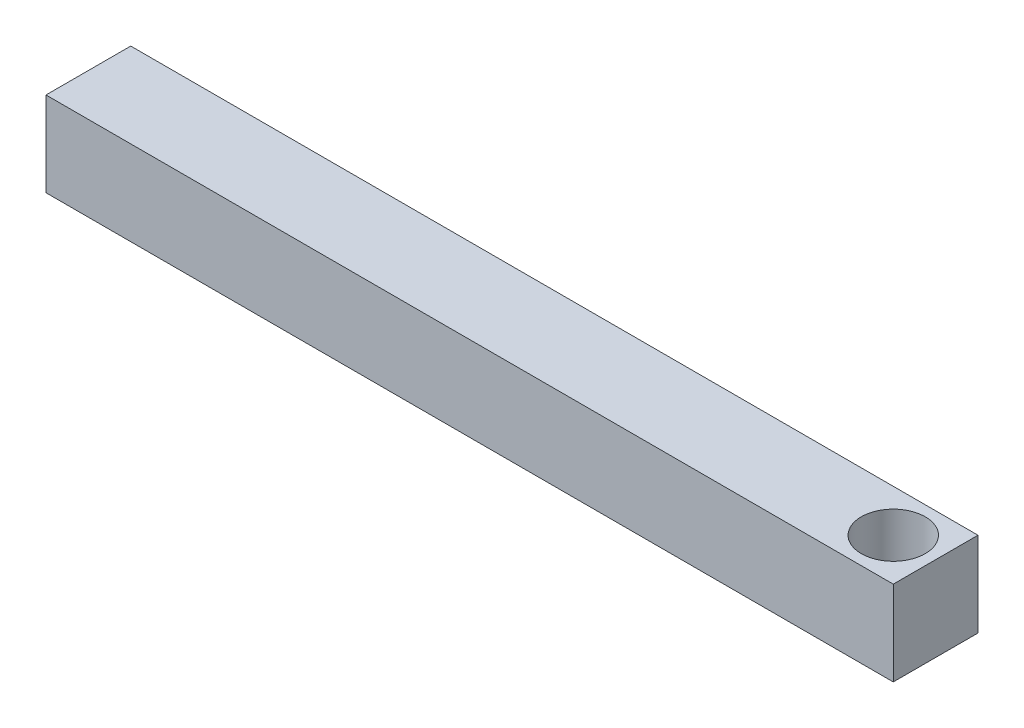
SolidWorks part; units mm, degrees
ref_plane "Front Plane" through (0, 0, 0) normal (0, 0, 1) x (1, 0, 0)
ref_plane "Top Plane" through (0, 0, 0) normal (0, 1, 0) x (1, 0, 0)
ref_plane "Right Plane" through (0, 0, 0) normal (1, 0, 0) x (0, 0, -1)
sketch "Sketch1" plane through (0, 0, 0) normal (0, 1, 0) x (1, 0, 0)
  line L1 (-39.7876, 8.6878) -> (87.2124, 8.6878)
  line L2 (-39.7876, 8.6878) -> (-39.7876, -4.0122)
  line L3 (-39.7876, -4.0122) -> (87.2124, -4.0122)
  line L4 (87.2124, 8.6878) -> (87.2124, -4.0122)
  dimension "D1" = 127
  dimension "D2" = 12.7
extrude "Boss-Extrude4" add sketch "Sketch1" along normal blind 12.7
sketch "Sketch6" plane through (0, 12.7, 0) normal (0, 1, 0) x (1, 0, 0)
  line L0 (87.2124, -4.0122) -> (87.2124, 8.6878) construction
  line L1 (87.2124, 8.6878) -> (-39.7876, 8.6878) construction
  circle A0 centre (80.8624, 2.3378) radius 4.7943
  point P2 (87.2124, 2.3378)
  dimension "D1" = 6.35
  dimension "D2" = 6.35
extrude "Cut-Extrude2" cut sketch "Sketch6" against normal blind 12.7
